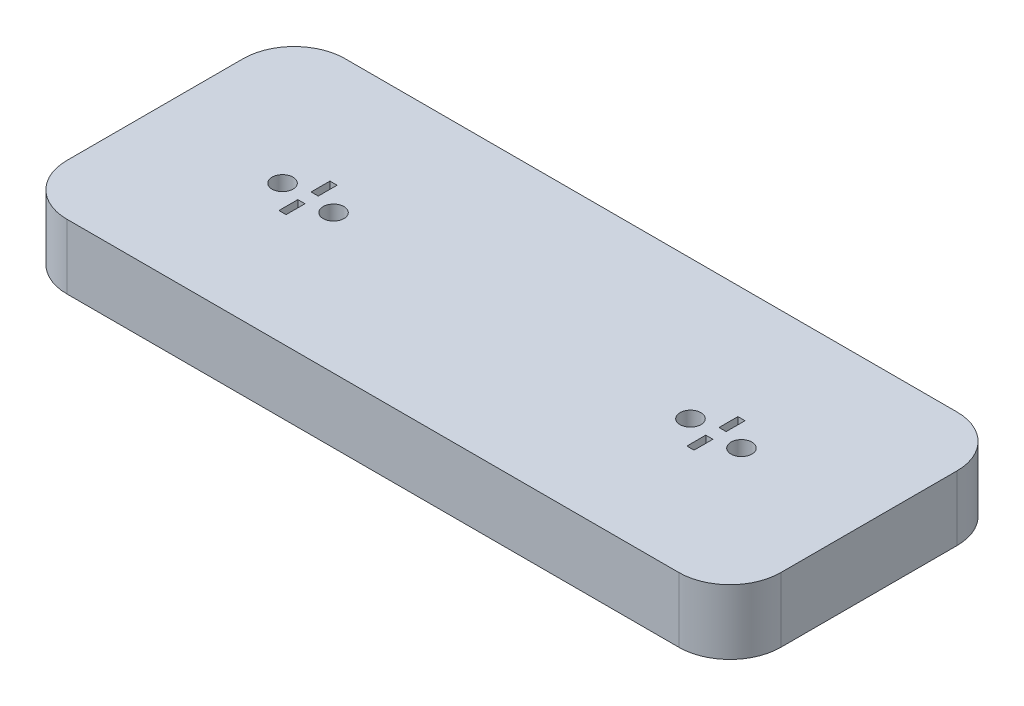
SolidWorks part; units mm, degrees
ref_plane "Front Plane" through (0, 0, 0) normal (0, 0, 1) x (1, 0, 0)
ref_plane "Top Plane" through (0, 0, 0) normal (0, 1, 0) x (1, 0, 0)
ref_plane "Right Plane" through (0, 0, 0) normal (1, 0, 0) x (0, 0, -1)
sketch "Sketch1" plane through (0, 0, 0) normal (0, 1, 0) x (1, 0, 0)
  line L1 (5, 0) -> (65, 0)
  line L2 (0, 5) -> (0, 22.27)
  line L3 (5, 27.27) -> (65, 27.27)
  line L4 (70, 5) -> (70, 22.27)
  arc A0 (5, 0) -> (0, 5) centre (5, 5) cw
  arc A1 (65, 0) -> (70, 5) centre (65, 5) ccw
  arc A2 (65, 27.27) -> (70, 22.27) centre (65, 22.27) cw
  arc A3 (0, 22.27) -> (5, 27.27) centre (5, 22.27) cw
  point P7 (0, 0)
  point P10 (70, 0)
  point P13 (70, 27.27)
  dimension "D3" = 5
  dimension "D1" = 70
  dimension "D2" = 27.27
extrude "Boss-Extrude1" add sketch "Sketch1" along normal blind 6.35
sketch "Sketch2" plane through (0, 6.35, 0) normal (0, 1, 0) x (1, 0, 0)
  line L0 (0, 13.635) -> (70, 13.635) construction
  line L1 (10, 18.635) -> (20, 18.635) construction
  line L2 (10, 18.635) -> (10, 8.635) construction
  line L3 (10, 8.635) -> (20, 8.635) construction
  line L4 (20, 18.635) -> (20, 8.635) construction
  line L5 (50, 18.635) -> (60, 18.635) construction
  line L6 (50, 18.635) -> (50, 8.635) construction
  line L7 (50, 8.635) -> (60, 8.635) construction
  line L8 (60, 18.635) -> (60, 8.635) construction
  line L9 (0, 22.27) -> (0, 5) construction
  line L10 (70, 5) -> (70, 22.27) construction
  line L11 (10, 13.635) -> (20, 13.635) construction
  line L12 (15, 18.635) -> (15, 8.635) construction
  line L13 (50, 13.635) -> (60, 13.635) construction
  line L14 (55, 18.635) -> (55, 8.635) construction
  line L16 (14.65, 16.135) -> (15.35, 16.135)
  line L17 (14.65, 16.135) -> (14.65, 14.285)
  line L18 (14.65, 14.285) -> (15.35, 14.285)
  line L19 (15.35, 16.135) -> (15.35, 14.285)
  line L20 (14.65, 16.135) -> (15.35, 14.285) construction
  line L21 (14.65, 14.285) -> (15.35, 16.135) construction
  line L22 (14.65, 12.985) -> (15.35, 12.985)
  line L23 (14.65, 12.985) -> (14.65, 11.135)
  line L24 (14.65, 11.135) -> (15.35, 11.135)
  line L25 (15.35, 12.985) -> (15.35, 11.135)
  line L26 (14.65, 12.985) -> (15.35, 11.135) construction
  line L27 (14.65, 11.135) -> (15.35, 12.985) construction
  line L28 (54.65, 12.985) -> (55.35, 12.985)
  line L29 (54.65, 12.985) -> (54.65, 11.135)
  line L30 (54.65, 11.135) -> (55.35, 11.135)
  line L31 (55.35, 12.985) -> (55.35, 11.135)
  line L32 (54.65, 12.985) -> (55.35, 11.135) construction
  line L33 (54.65, 11.135) -> (55.35, 12.985) construction
  line L34 (54.65, 14.285) -> (55.35, 14.285)
  line L35 (54.65, 14.285) -> (54.65, 16.135)
  line L36 (54.65, 16.135) -> (55.35, 16.135)
  line L37 (55.35, 14.285) -> (55.35, 16.135)
  line L38 (54.65, 14.285) -> (55.35, 16.135) construction
  line L39 (54.65, 16.135) -> (55.35, 14.285) construction
  circle A0 centre (12.5, 13.635) radius 1.025
  circle A1 centre (17.5, 13.635) radius 1.025
  circle A2 centre (52.5, 13.635) radius 1.025
  circle A3 centre (57.5, 13.635) radius 1.025
  point P30 (15, 15.21)
  point P35 (15, 12.06)
  point P40 (55, 12.06)
  point P45 (55, 15.21)
  dimension "D6" = 2.05
  dimension "D7" = 2.05
  dimension "D11" = 2.05
  dimension "D12" = 2.05
  dimension "D1" = 10
  dimension "D2" = 10
  dimension "D3" = 10
  dimension "D4" = 10
  dimension "D5" = 10
  dimension "D8" = 2.5
  dimension "D9" = 2.5
  dimension "D10" = 10
  dimension "D13" = 2.5
  dimension "D14" = 2.5
  dimension "D15" = 0.7
  dimension "D16" = 0.7
  dimension "D17" = 0.7
  dimension "D18" = 0.7
  dimension "D19" = 1.3
  dimension "D20" = 1.85
  dimension "D21" = 2.5
  dimension "D22" = 2.5
  dimension "D23" = 1.3
  dimension "D24" = 1.85
  dimension "D25" = 2.5
  dimension "D26" = 2.5
extrude "Cut-Extrude1" cut sketch "Sketch2" against normal blind 6.35
